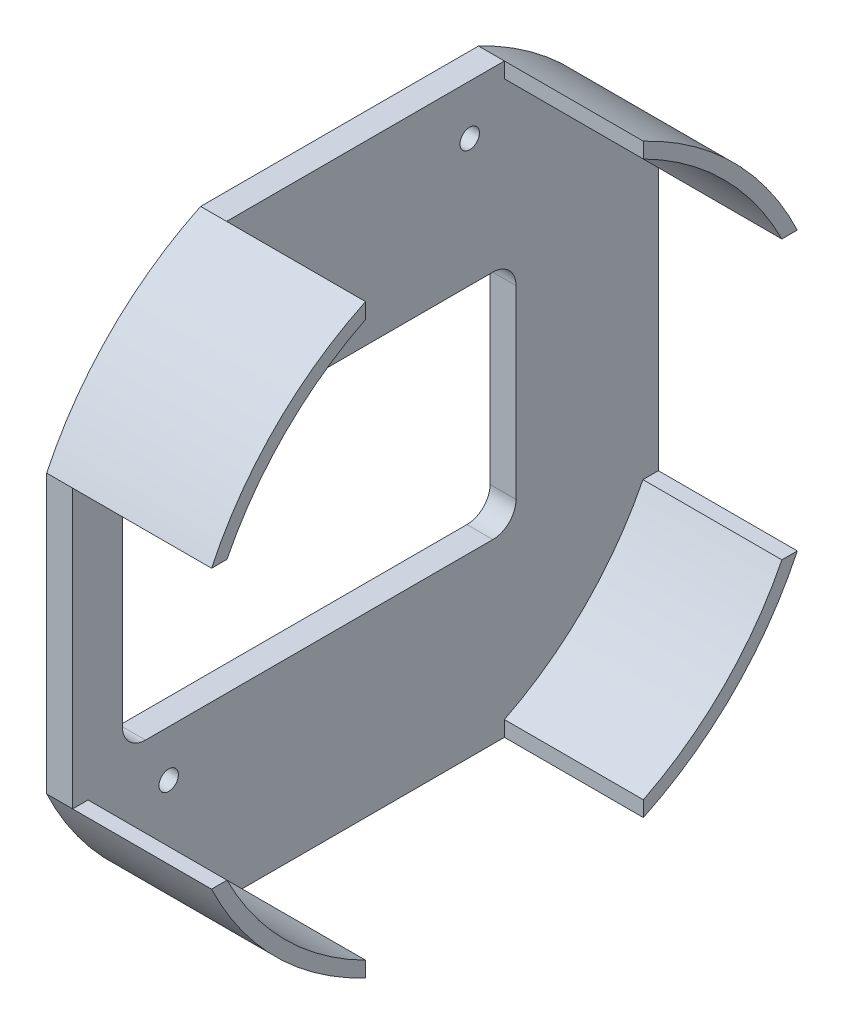
SolidWorks part; units mm, degrees
material "ﾎﾟﾘｴﾁﾚﾝｲﾐﾝ(PEI)"
ref_plane "正面" through (0, 0, 0) normal (0, 0, 1) x (1, 0, 0)
ref_plane "平面" through (0, 0, 0) normal (0, 1, 0) x (1, 0, 0)
ref_plane "右側面" through (0, 0, 0) normal (1, 0, 0) x (0, 0, -1)
sketch "ｽｹｯﾁ1" plane through (0, 0, 0) normal (1, 0, 0) x (0, 0, -1)
  line L0 (0, 0) -> (0, 52.5) construction
  line L1 (0, 52.5) -> (-32.5, 52.5) construction
  line L2 (0, 0) -> (10, 0) construction
  line L3 (-42.5, 25) -> (42.5, 25)
  line L4 (-42.5, 25) -> (-42.5, -25)
  line L5 (-42.5, -25) -> (42.5, -25)
  line L6 (42.5, 25) -> (42.5, -25)
  line L7 (-42.5, 25) -> (42.5, -25) construction
  line L8 (-42.5, -25) -> (42.5, 25) construction
  line L9 (-32.5, 52.5) -> (-32.5, -35) construction
  circle A2 centre (-32.5, 52.5) radius 2.1 construction
  circle A3 centre (32.5, 52.5) radius 2.1
  circle A4 centre (10, 0) radius 70
  circle A5 centre (-32.5, -35) radius 2.1
  dimension "D1" = 140
  dimension "D2" = 10
  dimension "D3" = 4.2
  dimension "D4" = 52.5
  dimension "D5" = 65
  dimension "D6" = 85
  dimension "D7" = 50
  dimension "D8" = 87.5
extrude "ﾎﾞｽ - 押し出し2" add sketch "ｽｹｯﾁ1" along normal blind 5.6
sketch "ｽｹｯﾁ2" plane through (5.6, 0, 0) normal (1, 0, 0) x (0, 0, -1)
  line L0 (-53.2456, 30) -> (-49.9083, 30)
  line L1 (10, 70) -> (10, 0) construction
  line L2 (10, 0) -> (80, 0) construction
  line L3 (-53.2456, -30) -> (-49.9083, -30)
  line L4 (40, 63.2456) -> (40, 59.9083)
  line L5 (-20, 63.2456) -> (-20, 59.9083)
  line L6 (-20, 59.9083) -> (-20, 30) construction
  line L7 (-20, 30) -> (-20, -30) construction
  line L8 (-49.9083, 30) -> (-20, 30) construction
  line L9 (69.9083, 30) -> (73.2456, 30)
  line L10 (-20, 30) -> (10, 30) construction
  line L11 (10, 30) -> (40, 30) construction
  line L12 (40, 30) -> (69.9083, 30) construction
  line L13 (40, -30) -> (69.9083, -30) construction
  line L14 (69.9083, -30) -> (73.2456, -30)
  line L15 (-20, -30) -> (40, -30) construction
  line L16 (-49.9083, -30) -> (-20, -30) construction
  line L17 (-20, -30) -> (-20, -59.9083) construction
  line L18 (-20, -59.9083) -> (-20, -63.2456)
  line L19 (40, -30) -> (40, -59.9083) construction
  line L20 (40, -59.9083) -> (40, -63.2456)
  line L21 (40, 59.9083) -> (40, 30) construction
  line L22 (40, 0) -> (40, -30) construction
  line L23 (40, 30) -> (40, 0) construction
  arc A0 (-49.9083, -30) -> (-20, -59.9083) centre (10, 0) ccw
  circle A1 centre (10, 0) radius 70
  arc A2 (-53.2456, -30) -> (-20, -63.2456) centre (10, 0) ccw
  arc A3 (-53.2456, 30) -> (-53.2456, -30) centre (10, 0) ccw construction
  circle A4 centre (10, 0) radius 70 construction
  arc A5 (-49.9083, 30) -> (-49.9083, -30) centre (10, 0) ccw construction
  circle A6 centre (10, 0) radius 67 construction
  arc A7 (80, 0) -> (73.2456, 30) centre (10, 0) ccw construction
  arc A8 (73.2456, 30) -> (40, 63.2456) centre (10, 0) ccw
  arc A9 (77, 0) -> (69.9083, 30) centre (10, 0) ccw construction
  arc A10 (69.9083, 30) -> (40, 59.9083) centre (10, 0) ccw
  arc A11 (73.2456, -30) -> (80, 0) centre (10, 0) ccw construction
  arc A12 (69.9083, -30) -> (77, 0) centre (10, 0) ccw construction
  arc A13 (-20, -63.2456) -> (40, -63.2456) centre (10, 0) ccw construction
  arc A14 (40, -63.2456) -> (73.2456, -30) centre (10, 0) ccw
  arc A15 (-20, -59.9083) -> (40, -59.9083) centre (10, 0) ccw construction
  arc A16 (40, -59.9083) -> (69.9083, -30) centre (10, 0) ccw
  arc A17 (40, 63.2456) -> (10, 70) centre (10, 0) ccw construction
  arc A18 (-20, 63.2456) -> (-53.2456, 30) centre (10, 0) ccw
  arc A19 (40, 59.9083) -> (10, 67) centre (10, 0) ccw construction
  arc A20 (-20, 59.9083) -> (-49.9083, 30) centre (10, 0) ccw
  arc A21 (10, 70) -> (-20, 63.2456) centre (10, 0) ccw construction
  arc A22 (10, 67) -> (-20, 59.9083) centre (10, 0) ccw construction
  dimension "D3" = 60
  dimension "D4" = 60
  dimension "D1" = 0
  dimension "D2" = 3
extrude "ﾎﾞｽ - 押し出し3" add sketch "ｽｹｯﾁ2" along normal blind 30
sketch "ｽｹｯﾁ3" plane through (5.6, 0, 0) normal (1, 0, 0) x (0, 0, -1)
  line L0 (-20, 63.2456) -> (40, 63.2456)
  line L1 (73.2456, 30) -> (73.2456, -30)
  line L2 (40, -63.2456) -> (-20, -63.2456)
  line L3 (-53.2456, -30) -> (-53.2456, 30)
  line L8 (69.9083, -30) -> (73.2456, -30)
  line L9 (73.2456, 30) -> (69.9083, 30)
  line L10 (40, 59.9083) -> (40, 63.2456)
  line L11 (-20, 63.2456) -> (-20, 59.9083)
  line L12 (-49.9083, 30) -> (-53.2456, 30)
  line L13 (-53.2456, -30) -> (-49.9083, -30)
  line L14 (-20, -59.9083) -> (-20, -63.2456)
  line L15 (40, -63.2456) -> (40, -59.9083)
  line L16 (69.9083, -30) -> (73.2456, -30)
  line L17 (73.2456, 30) -> (69.9083, 30)
  line L18 (40, 59.9083) -> (40, 63.2456)
  line L19 (-20, 63.2456) -> (-20, 59.9083)
  line L20 (-49.9083, 30) -> (-53.2456, 30)
  line L21 (-53.2456, -30) -> (-49.9083, -30)
  line L22 (-20, -59.9083) -> (-20, -63.2456)
  line L23 (40, -63.2456) -> (40, -59.9083)
  arc A8 (40, -59.9083) -> (69.9083, -30) centre (10, 0) ccw
  arc A9 (73.2456, -30) -> (73.2456, 30) centre (10, 0) ccw
  arc A10 (69.9083, 30) -> (40, 59.9083) centre (10, 0) ccw
  arc A11 (40, 63.2456) -> (-20, 63.2456) centre (10, 0) ccw
  arc A12 (-20, 59.9083) -> (-49.9083, 30) centre (10, 0) ccw
  arc A13 (-53.2456, 30) -> (-53.2456, -30) centre (10, 0) ccw
  arc A14 (-49.9083, -30) -> (-20, -59.9083) centre (10, 0) ccw
  arc A15 (-20, -63.2456) -> (40, -63.2456) centre (10, 0) ccw
  arc A16 (40, -59.9083) -> (69.9083, -30) centre (10, 0) ccw
  arc A17 (73.2456, -30) -> (73.2456, 30) centre (10, 0) ccw
  arc A18 (69.9083, 30) -> (40, 59.9083) centre (10, 0) ccw
  arc A19 (40, 63.2456) -> (-20, 63.2456) centre (10, 0) ccw
  arc A20 (-20, 59.9083) -> (-49.9083, 30) centre (10, 0) ccw
  arc A21 (-53.2456, 30) -> (-53.2456, -30) centre (10, 0) ccw
  arc A22 (-49.9083, -30) -> (-20, -59.9083) centre (10, 0) ccw
  arc A23 (-20, -63.2456) -> (40, -63.2456) centre (10, 0) ccw
  arc M25 (73.2456, -30) -> (73.2456, 30) centre (10, 0) ccw
  arc M29 (40, 63.2456) -> (-20, 63.2456) centre (10, 0) ccw
  arc M33 (-53.2456, 30) -> (-53.2456, -30) centre (10, 0) ccw
  arc M37 (-20, -63.2456) -> (40, -63.2456) centre (10, 0) ccw
  dimension "D1" = 0
extrude "ｶｯﾄ - 押し出し1" cut sketch "ｽｹｯﾁ3" against normal through all contours L0 M29 | L3 M33 | L2 M37 | L1 M25
fillet "ﾌｨﾚｯﾄ1" radius 5 4 edges at (2.8, 25, 42.5) (2.8, -25, 42.5) (2.8, 25, -42.5) (2.8, -25, -42.5)
